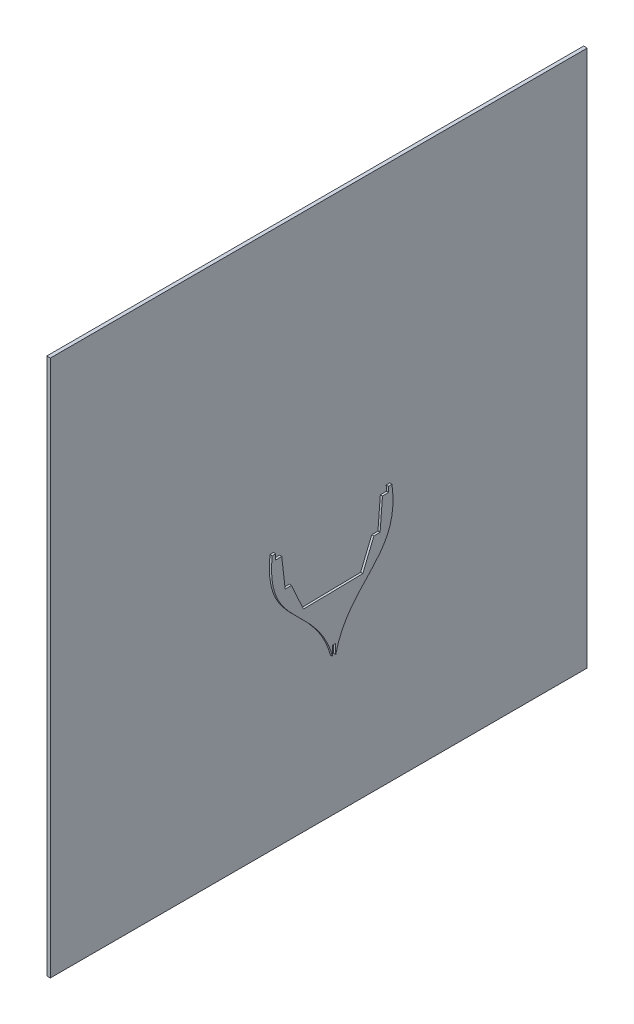
SolidWorks part; units mm, degrees
ref_plane "Plan de face" through (0, 0, 0) normal (0, 0, 1) x (1, 0, 0)
ref_plane "Plan de dessus" through (0, 0, 0) normal (0, 1, 0) x (1, 0, 0)
ref_plane "Plan de droite" through (0, 0, 0) normal (1, 0, 0) x (0, 0, -1)
sketch "Esquisse1" plane through (0, 0, 0) normal (0, 0, 1) x (1, 0, 0)
  point P0 (-20, 0)
  dimension "D1" = 20
sketch3d "Esquisse3D1"
  line L1 (-20, 1121.2893, 777.275) -> (-20, 1121.2893, -722.725)
  line L2 (-20, 1121.2893, 777.275) -> (-20, -378.7107, 777.275)
  line L3 (-20, -378.7107, 777.275) -> (-20, -378.7107, -722.725)
  line L4 (-20, 1121.2893, -722.725) -> (-20, -378.7107, -722.725)
  dimension "D1" = 1500
  dimension "D2" = 1500
extrude "Boss.-Extru.2" add sketch "Esquisse3D1" along direction (1, 0, 0) on the side of the normal blind 10 contours L2 L1 L4 L3
sketch "Esquisse4" plane through (-10, 0, 0) normal (1, 0, 0) x (0, 0, -1)
  line L0 (0, 0) -> (-7.701, 425.1082) construction
  line L1 (169.3944, 339.9131) -> (-188.5193, 333.4294) construction
  line L2 (-187.2006, 249.23) -> (169.0622, 255.6839) construction
  line L3 (-144.268, 175.2448) -> (126.4811, 180.1495) construction
sketch "Esquisse5" plane through (0, 0, 0) normal (1, 0, 0) x (0, 0, -1)
  line L0 (-7.701, 425.1082) -> (0, 0) construction
  line L2 (0, 0) -> (3.955, 18.2202) construction
  line L3 (3.955, 18.2202) -> (19.6239, 195.4276) construction
  line L4 (19.6239, 195.4276) -> (189.784, 145.8872) construction
  line L5 (189.784, 145.8872) -> (161.0193, 354.9544) construction
  line L8 (161.0193, 354.9544) -> (151.0193, 354.7733)
  line L9 (151.0193, 354.7733) -> (151.9551, 339.5972)
  line L10 (169.3944, 339.9131) -> (-188.5193, 333.4294) construction
  line L11 (151.9551, 339.5972) -> (134.6025, 339.2829)
  line L12 (134.6025, 339.2829) -> (128.0103, 254.9402)
  line L13 (-187.2006, 249.23) -> (169.0622, 255.6839) construction
  line L14 (128.0103, 254.9402) -> (110.594, 254.6247)
  line L15 (110.594, 254.6247) -> (79.5764, 179.2998)
  line L16 (-144.268, 175.2448) -> (126.4811, 180.1495) construction
  line L17 (79.5764, 179.2998) -> (-86.0182, 176.3)
  line L18 (0, 0) -> (-4.6123, 18.065) construction
  line L19 (-4.6123, 18.065) -> (-26.6892, 194.5887) construction
  line L20 (-26.6892, 194.5887) -> (-194.9433, 138.9177) construction
  line L21 (-194.9433, 138.9177) -> (-173.7697, 348.8896) construction
  line L22 (-119.7437, 250.452) -> (-86.0182, 176.3)
  line L23 (-137.1599, 250.1365) -> (-119.7437, 250.452)
  line L24 (-146.8026, 334.1851) -> (-137.1599, 250.1365)
  line L25 (-164.1552, 333.8707) -> (-146.8026, 334.1851)
  line L26 (-163.7697, 349.0708) -> (-164.1552, 333.8707)
  line L27 (-173.7697, 348.8896) -> (-163.7697, 349.0708)
  spline S0 degree 4 poles (0, 0) (3.955, 18.2202) (19.6239, 195.4276) (189.784, 145.8872) (161.0193, 354.9544) knots 0 0 0 0 0 1 1 1 1 1
  spline S1 degree 4 poles (0, 0) (-4.6123, 18.065) (-26.6892, 194.5887) (-194.9433, 138.9177) (-173.7697, 348.8896) knots 0 0 0 0 0 1 1 1 1 1
  point P30 (-3.2209, 177.7999)
  dimension "D1" = 10
extrude "Boss.-Extru.3" add sketch "Esquisse5" along normal blind 6 separate body
sketch "Esquisse6" plane through (6, 0, 0) normal (1, 0, 0) x (0, 0, -1)
  line L0 (-4.8863, 21.2419) -> (-5.3754, 48.2419)
  line L1 (-5.3754, 48.2419) -> (3.6246, 48.405)
  line L2 (3.6246, 48.405) -> (4.1137, 21.405)
  line L3 (4.1137, 21.405) -> (117.0633, -47.527)
  line L4 (117.0633, -47.527) -> (-85.2277, -65.22)
  line L5 (-85.2277, -65.22) -> (-4.8863, 21.2419)
  line L6 (-4.8863, 21.2419) -> (4.1137, 21.405) construction
  line L7 (-144.268, 175.2448) -> (126.4811, 180.1495) construction
  spline S0 degree 4 poles (-173.7697, 348.8896) (-194.9433, 138.9177) (-26.6892, 194.5887) (-4.6123, 18.065) (0, 0) knots 0 0 0 0 0 1 1 1 1 1 construction
  spline S1 degree 4 poles (0, 0) (3.955, 18.2202) (19.6239, 195.4276) (189.784, 145.8872) (161.0193, 354.9544) knots 0 0 0 0 0 1 1 1 1 1 construction
  dimension "D1" = 9
  dimension "D2" = 27
extrude "Enlèv. mat.-Extru.1" cut sketch "Esquisse6" against normal blind 6
